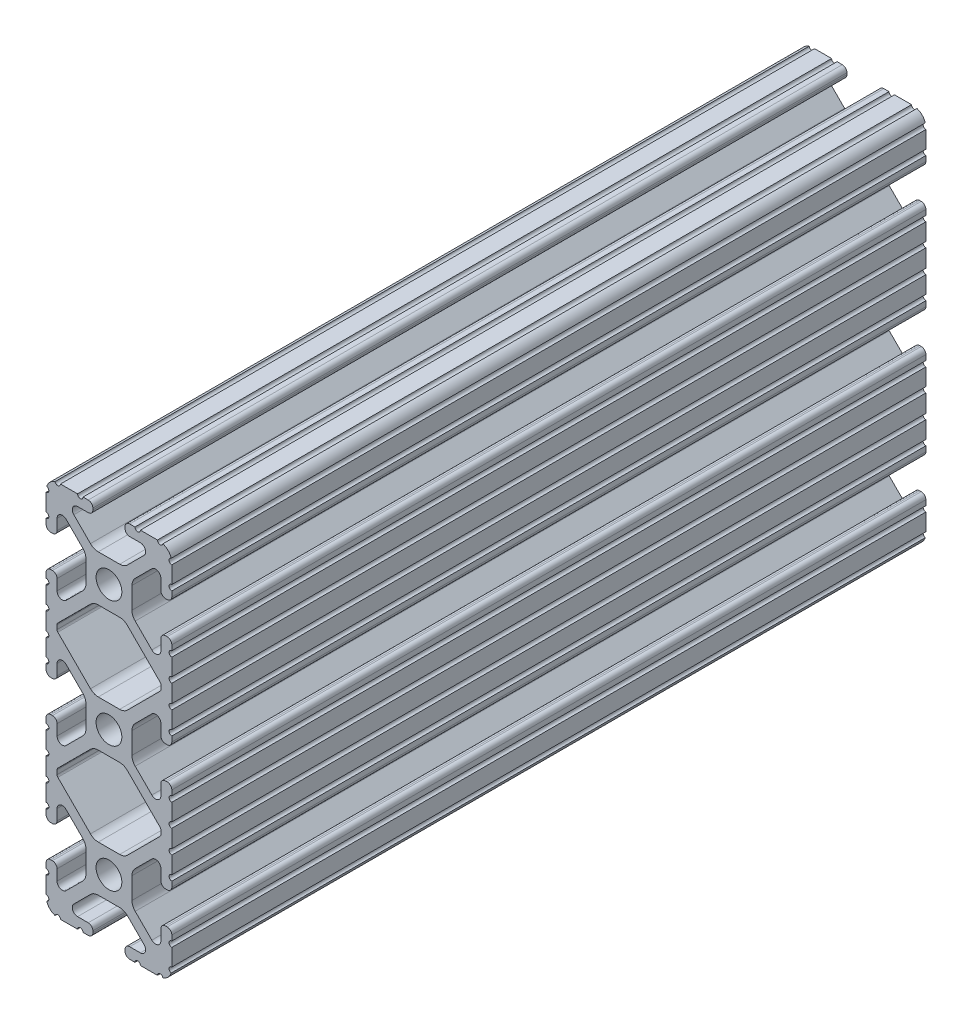
SolidWorks part; units mm, degrees
material "6061-T6 (SS)"
ref_plane "Front Plane" through (0, 0, 0) normal (0, 0, 1) x (1, 0, 0)
ref_plane "Top Plane" through (0, 0, 0) normal (0, 1, 0) x (1, 0, 0)
ref_plane "Right Plane" through (0, 0, 0) normal (1, 0, 0) x (0, 0, -1)
sketch "Sketch2" plane through (0, 0, 0) normal (0, 0, 1) x (1, 0, 0)
  line L0 (0, 38.1) -> (0, -38.1) construction
  line L1 (-12.7, 0) -> (12.7, 0) construction
  line L2 (3.2512, -38.1) -> (12.7, -38.1)
  line L3 (12.7, -38.1) -> (12.7, -28.6512)
  line L4 (3.2512, -38.1) -> (3.2512, -35.8902)
  line L5 (3.2512, -35.8902) -> (8.9276, -35.8902)
  line L6 (8.9276, -35.8902) -> (3.0856, -30.0482)
  line L7 (0, -25.4) -> (12.7, -38.1) construction
  line L8 (12.7, -28.6512) -> (10.4902, -28.6512)
  line L9 (10.4902, -28.6512) -> (10.4902, -34.3276)
  line L10 (10.4902, -34.3276) -> (4.6482, -28.4856)
  circle A0 centre (0, -25.4) radius 2.6035
  arc A1 (6.3485, -35.8902) -> (7.1039, -34.0665) centre (6.3485, -34.8219) ccw construction
  point P8 (0, -30.0482)
  dimension "Center Hole Diameter" = 5.207
  dimension "Rail Height" = 76.2
  dimension "Rail Width" = 25.4
  dimension "T-Slot Width" = 6.5024
  dimension "Slot Inner Width" = 14.8336
  dimension "Thickness" = 2.2098
  dimension "Slot Depth" = 5.842
  dimension "D1" = 2.2098
  dimension "D2" = 50.8
sketch "Sketch3" plane through (0, 0, 0) normal (1, 0, 0) x (0, 0, -1)
  line L0 (-152.4, -38.1) -> (152.4, -38.1) construction
  line L1 (-127, 0) -> (127, 0) construction
  dimension "D1" = 25.4
  dimension "Length" = 304.8
sketch "Sketch4" plane through (0, 0, 0) normal (0, 0, 1) x (1, 0, 0)
  line L0 (4.1904, -38.1) -> (10.1173, -38.1)
  line L1 (3.2512, -38.1) -> (12.7, -38.1) construction
  line L2 (3.2512, -38.1) -> (3.2512, -35.8902) construction
  line L3 (3.2512, -35.8902) -> (8.9276, -35.8902) construction
  line L4 (3.2512, -36.8294) -> (3.2512, -37.1608)
  line L5 (4.1904, -35.8902) -> (6.3485, -35.8902)
  line L6 (0, -30.0482) -> (2.164, -30.0482)
  line L7 (8.9276, -35.8902) -> (3.0856, -30.0482) construction
  line L8 (3.7373, -30.6999) -> (7.1039, -34.0665)
  line L9 (12.7, -38.1) -> (12.7, -28.6512) construction
  line L10 (10.4902, -34.3276) -> (4.6482, -28.4856) construction
  line L11 (10.4902, -28.6512) -> (10.4902, -34.3276) construction
  line L12 (10.4902, -31.7485) -> (10.4902, -29.5904)
  line L13 (12.7, -28.6512) -> (10.4902, -28.6512) construction
  line L14 (11.4294, -28.6512) -> (11.7608, -28.6512)
  line L15 (12.7, -29.5904) -> (12.7, -35.5173)
  line L16 (8.6665, -32.5039) -> (5.2999, -29.1373)
  line L17 (4.6482, -25.4) -> (4.6482, -27.564)
  line L19 (0, -30.0482) -> (0, -28.0035)
  line L20 (0, 38.1) -> (0, -38.1) construction
  line L21 (4.6482, -25.4) -> (2.6035, -25.4)
  arc A0 (3.2512, -37.1608) -> (4.1904, -38.1) centre (4.1904, -37.1608) ccw
  circle A1 centre (0, -25.4) radius 2.6035 construction
  arc A2 (3.2512, -36.8294) -> (4.1904, -35.8902) centre (4.1904, -36.8294) cw
  arc A3 (6.3485, -35.8902) -> (7.1039, -34.0665) centre (6.3485, -34.8219) ccw
  arc A4 (2.164, -30.0482) -> (3.7373, -30.6999) centre (2.164, -32.2732) cw
  arc A5 (10.1173, -38.1) -> (12.7, -35.5173) centre (10.1173, -35.5173) ccw
  arc A6 (8.6665, -32.5039) -> (10.4902, -31.7485) centre (9.4219, -31.7485) ccw
  arc A7 (10.4902, -29.5904) -> (11.4294, -28.6512) centre (11.4294, -29.5904) cw
  arc A8 (11.7608, -28.6512) -> (12.7, -29.5904) centre (11.7608, -29.5904) cw
  arc A9 (5.2999, -29.1373) -> (4.6482, -27.564) centre (6.8732, -27.564) cw
  arc A11 (0, -28.0035) -> (2.6035, -25.4) centre (0, -25.4) ccw
  dimension "D1" = 2.5827
  dimension "D2" = 2.225
  dimension "D3" = 0.9392
extrude "Boss-Extrude1" add sketch "Sketch4" along normal mid plane 152.4
sketch "Sketch5" plane through (0, 0, 0) normal (0, 0, 1) x (1, 0, 0)
  line L0 (3.2512, -38.1) -> (12.7, -38.1) construction
  line L1 (4.1904, -35.8902) -> (6.3485, -35.8902) construction
  line L3 (0, -25.4) -> (12.7, -38.1) construction
  line L4 (6.3485, -35.8902) -> (6.3485, -38.1) construction
  line L5 (8.9276, -35.8902) -> (3.0856, -30.0482) construction
  circle A0 centre (10.3562, -38.1) radius 0.5524
  circle A1 centre (5.796, -38.1) radius 0.5524
  circle A2 centre (12.7, -35.7562) radius 0.5525
  circle A3 centre (12.7, -31.196) radius 0.5525
  point P10 (5.2694, -35.8902)
  point P12 (9.4219, -31.7485)
  dimension "D1" = 1.1049
extrude "Cut-Extrude1" cut sketch "Sketch5" against normal through all both and the other way through all
mirror "Mirror1" about plane through (4.6482, -25.4, 76.2) normal (0, -1, 0) of bodies 137 134
sketch "Sketch6" plane through (0, 0, 0) normal (0, 0, 1) x (1, 0, 0)
  line L0 (12.7, -14.4914) -> (12.7, -12.7)
  line L1 (12.7, -12.7) -> (9.8037, -12.7)
  line L3 (9.8037, -12.7) -> (9.8037, -15.5963)
  line L4 (9.8037, -15.5963) -> (12.7, -15.5963)
  line L5 (6.3485, -12.7) -> (9.8037, -12.7) construction
  circle A0 centre (12.7, -15.0438) radius 0.5525 construction
  arc A1 (12.7, -14.4914) -> (12.7, -15.5963) centre (12.7, -15.0438) ccw
  arc A4 (9.8037, -12.7) -> (10.8954, -12.82) centre (10.3562, -12.7) ccw construction
extrude "Boss-Extrude2" add sketch "Sketch6" along normal mid plane 152.4
sketch "Sketch7" plane through (0, 0, 0) normal (0, 0, 1) x (1, 0, 0)
  line L0 (5.4206, -18.4168) -> (10.3284, -13.509)
  line L1 (3.7373, -20.1001) -> (7.1039, -16.7335) construction
  line L2 (10.4902, -13.1184) -> (10.4902, -12.7)
  line L3 (0, -12.7) -> (10.4902, -12.7)
  line L5 (0, -12.7) -> (5.4206, -18.4168)
  line L7 (0, 38.1) -> (0, -38.1) construction
  line L8 (6.3485, -12.7) -> (12.7, -12.7) construction
  arc A0 (10.3284, -13.509) -> (10.4902, -13.1184) centre (9.9377, -13.1184) ccw
  circle A3 centre (12.7, -15.0438) radius 0.5525 construction
extrude "Cut-Extrude2" cut sketch "Sketch7" against normal through all both and the other way through all
mirror "Mirror2" about plane through (4.1904, -12.7, 76.2) normal (0, -1, 0) of bodies 139 135
other "SurfaceCut1"
mirror "Mirror3" about plane through (0, 0, 0) normal (1, 0, 0) of bodies 142 136
mirror "Mirror4" about plane through (0, 0, 0) normal (0, 1, 0) of bodies 140
equation "\"D1@Boss-Extrude1\" = \"azimuth_vertictal_rail_length\""
equation "\"D1@Sketch2\"=\"Thickness@Sketch2\""
equation "\"D2@Sketch4\"=\"Slot Inner Width@Sketch2\"*0.15"
equation "\"D1@Sketch4\"=\"D3@Sketch4\"*2.75"
equation "\"D3@Sketch4\"=\"Thickness@Sketch2\"*0.425"
equation "\"D1@Sketch5\"= \"Thickness@Sketch2\" * 0.5"
equation "\"D1@Boss-Extrude2\" = \"azimuth_vertictal_rail_length\""
equation "\"azimuth_horizontal_rail_length\"=12in"
equation "\"azimuth_vertictal_rail_length\"=6in"
equation "\"wall_screw_clearance_diameter\"=4.3mm"
